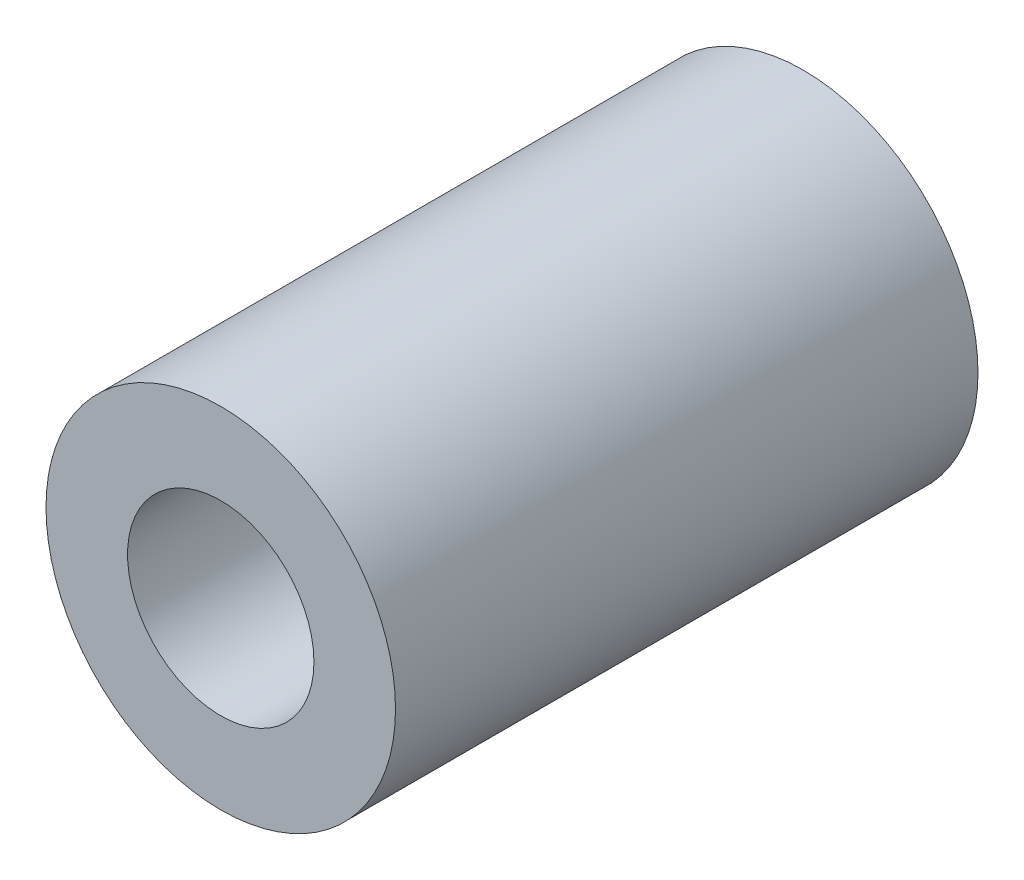
SolidWorks part; units mm, degrees
material "6063-T1"
ref_plane "Front Plane" through (0, 0, 0) normal (0, 0, 1) x (1, 0, 0)
ref_plane "Top Plane" through (0, 0, 0) normal (0, 1, 0) x (1, 0, 0)
ref_plane "Right Plane" through (0, 0, 0) normal (1, 0, 0) x (0, 0, -1)
sketch "Sketch1" plane through (0, 0, 0) normal (0, 0, 1) x (1, 0, 0)
  circle A0 centre (0, 0) radius 3
  circle A1 centre (0, 0) radius 1.6
  dimension "D1" = 6
  dimension "D2" = 3.2
extrude "Boss-Extrude1" add sketch "Sketch1" along normal blind 10
